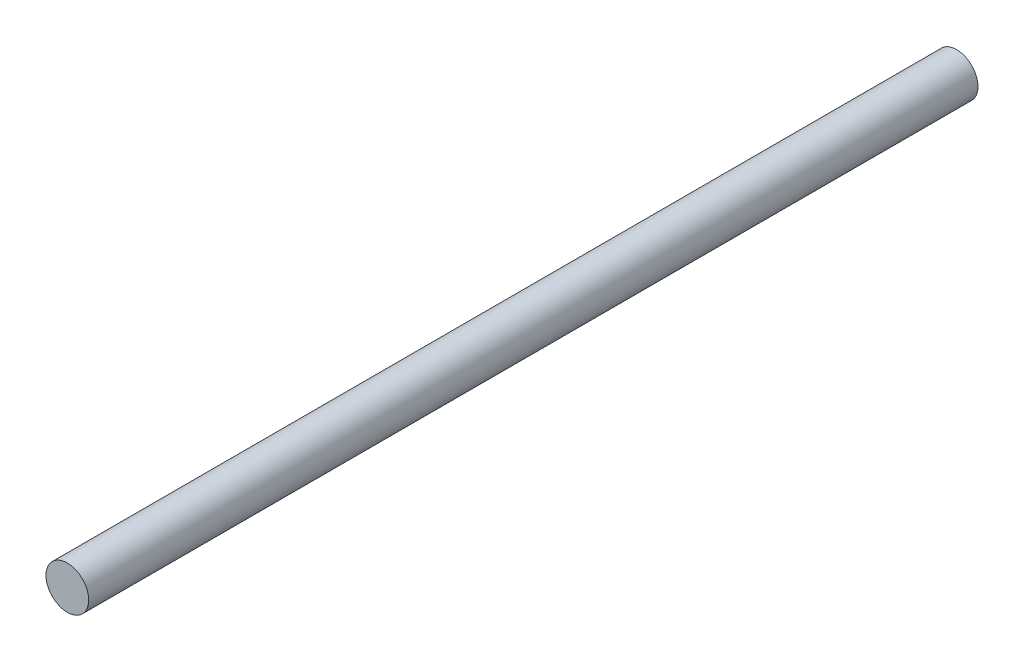
SolidWorks part; units mm, degrees
ref_plane "Front Plane" through (0, 0, 0) normal (0, 0, 1) x (1, 0, 0)
ref_plane "Top Plane" through (0, 0, 0) normal (0, 1, 0) x (1, 0, 0)
ref_plane "Right Plane" through (0, 0, 0) normal (1, 0, 0) x (0, 0, -1)
sketch "Sketch1" plane through (0, 0, 0) normal (0, 0, 1) x (1, 0, 0)
  circle A0 centre (0, 0) radius 3.9688
extrude "Boss-Extrude1" add sketch "Sketch1" along normal blind 165.1
